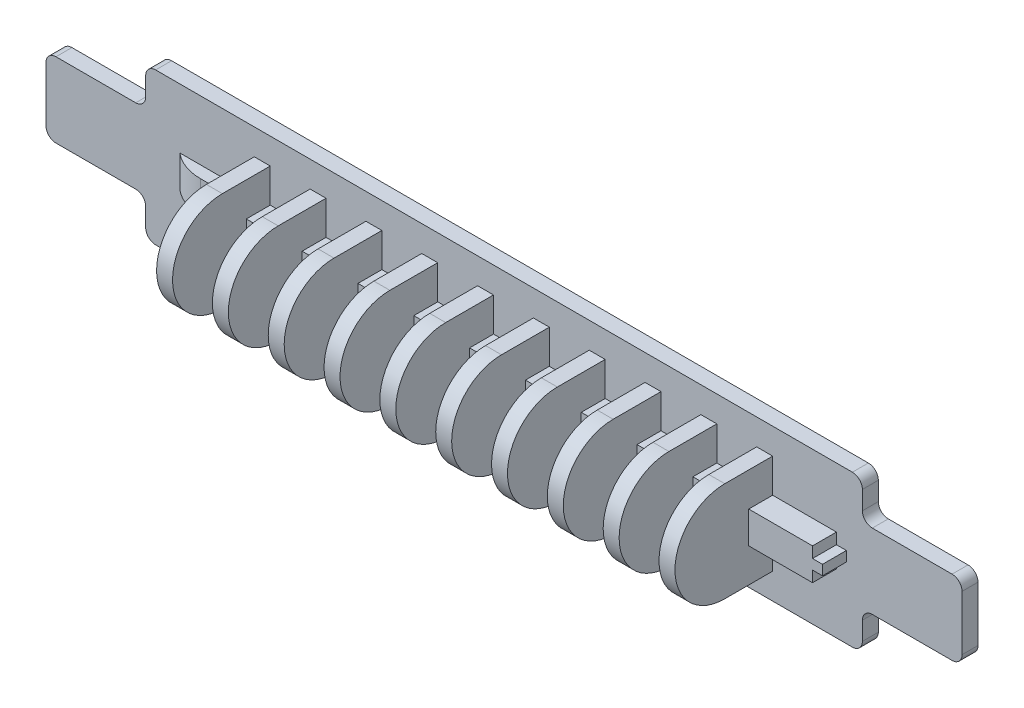
SolidWorks part; units mm, degrees
ref_plane "前视基准面" through (0, 0, 0) normal (0, 0, 1) x (1, 0, 0)
ref_plane "上视基准面" through (0, 0, 0) normal (0, 1, 0) x (1, 0, 0)
ref_plane "右视基准面" through (0, 0, 0) normal (1, 0, 0) x (0, 0, -1)
sketch "草图1" plane through (0, 0, 0) normal (0, 0, 1) x (1, 0, 0)
  line L1 (-44.9335, 9.5) -> (44.9335, 9.5)
  line L2 (-44.9335, 9.5) -> (-44.9335, -9.5)
  line L3 (-44.9335, -9.5) -> (44.9335, -9.5)
  line L4 (44.9335, 9.5) -> (44.9335, -9.5)
  line L5 (-44.9335, 9.5) -> (44.9335, -9.5) construction
  line L6 (-44.9335, -9.5) -> (44.9335, 9.5) construction
  point P0 (0, 0)
  dimension "D1" = 19
  dimension "D2" = 89.8669
extrude "凸台-拉伸1" add sketch "草图1" along normal blind 2
sketch "草图2" plane through (0, 0, 2) normal (0, 0, 1) x (1, 0, 0)
  line L0 (-44.9335, 0) -> (44.9335, 0) construction
  line L1 (-44.9335, 9.5) -> (-44.9335, -9.5) construction
  line L2 (44.9335, -9.5) -> (44.9335, 9.5) construction
  line L4 (31.6835, 6.25) -> (33.6835, 6.25)
  line L5 (31.6835, 6.25) -> (31.6835, -6.25)
  line L6 (31.6835, -6.25) -> (33.6835, -6.25)
  line L7 (33.6835, 6.25) -> (33.6835, -6.25)
  line L8 (31.6835, 6.25) -> (33.6835, -6.25) construction
  line L9 (31.6835, -6.25) -> (33.6835, 6.25) construction
  line L53 (24.6835, 6.25) -> (24.6835, -6.25)
  line L54 (24.6835, 6.25) -> (26.6835, 6.25)
  line L55 (26.6835, 6.25) -> (26.6835, -6.25)
  line L56 (24.6835, -6.25) -> (26.6835, -6.25)
  line L57 (17.6835, 6.25) -> (17.6835, -6.25)
  line L58 (17.6835, 6.25) -> (19.6835, 6.25)
  line L59 (19.6835, 6.25) -> (19.6835, -6.25)
  line L60 (17.6835, -6.25) -> (19.6835, -6.25)
  line L61 (10.6835, 6.25) -> (10.6835, -6.25)
  line L62 (10.6835, 6.25) -> (12.6835, 6.25)
  line L63 (12.6835, 6.25) -> (12.6835, -6.25)
  line L64 (10.6835, -6.25) -> (12.6835, -6.25)
  line L65 (3.6835, 6.25) -> (3.6835, -6.25)
  line L66 (3.6835, 6.25) -> (5.6835, 6.25)
  line L67 (5.6835, 6.25) -> (5.6835, -6.25)
  line L68 (3.6835, -6.25) -> (5.6835, -6.25)
  line L69 (-3.3165, 6.25) -> (-3.3165, -6.25)
  line L70 (-3.3165, 6.25) -> (-1.3165, 6.25)
  line L71 (-1.3165, 6.25) -> (-1.3165, -6.25)
  line L72 (-3.3165, -6.25) -> (-1.3165, -6.25)
  line L73 (-10.3165, 6.25) -> (-10.3165, -6.25)
  line L74 (-10.3165, 6.25) -> (-8.3165, 6.25)
  line L75 (-8.3165, 6.25) -> (-8.3165, -6.25)
  line L76 (-10.3165, -6.25) -> (-8.3165, -6.25)
  line L77 (-17.3165, 6.25) -> (-17.3165, -6.25)
  line L78 (-17.3165, 6.25) -> (-15.3165, 6.25)
  line L79 (-15.3165, 6.25) -> (-15.3165, -6.25)
  line L80 (-17.3165, -6.25) -> (-15.3165, -6.25)
  line L81 (-24.3165, 6.25) -> (-24.3165, -6.25)
  line L82 (-24.3165, 6.25) -> (-22.3165, 6.25)
  line L83 (-22.3165, 6.25) -> (-22.3165, -6.25)
  line L84 (-24.3165, -6.25) -> (-22.3165, -6.25)
  line L85 (-31.3165, 6.25) -> (-31.3165, -6.25)
  line L86 (-31.3165, 6.25) -> (-29.3165, 6.25)
  line L87 (-29.3165, 6.25) -> (-29.3165, -6.25)
  line L88 (-31.3165, -6.25) -> (-29.3165, -6.25)
  point P6 (32.6835, 0)
  dimension "D1" = 12.25
  dimension "D3" = 12.5
  dimension "D4" = 2
  dimension "D2" = 10
extrude "凸台-拉伸2" add sketch "草图2" along normal blind 6
sketch "草图3" plane through (0, 0, 2) normal (0, 0, 1) x (1, 0, 0)
  line L0 (-44.9335, 0) -> (44.9335, 0) construction
  line L1 (-44.9335, 9.5) -> (-44.9335, -9.5) construction
  line L2 (44.9335, -9.5) -> (44.9335, 9.5) construction
  line L6 (-29.3165, -2) -> (42.9335, -2)
  line L7 (42.9335, 2) -> (42.9335, -2)
  line L8 (-36.3165, 2) -> (42.9335, 2)
  line L9 (-29.3165, -2) -> (-36.3165, -2)
  line L12 (-36.3165, -2) -> (-36.3165, 2)
  dimension "D1" = 2
extrude "凸台-拉伸3" add sketch "草图3" along normal blind 3
sketch "草图4" plane through (0, 0, 8) normal (0, 0, 1) x (1, 0, 0)
  line L0 (-31.3165, 0) -> (33.6835, 0) construction
  line L101 (-31.3165, 6.25) -> (-31.3165, -6.25) construction
  line L102 (33.6835, -6.25) -> (33.6835, 6.25) construction
  line L103 (26.6835, 0) -> (26.6835, -6.25)
  line L104 (33.6835, 0) -> (31.6835, 0)
  line L105 (33.6835, 0) -> (33.6835, -6.25)
  line L106 (33.6835, -6.25) -> (31.6835, -6.25)
  line L107 (31.6835, 0) -> (31.6835, -6.25)
  line L108 (26.6835, 0) -> (24.6835, 0)
  line L109 (24.6835, 0) -> (24.6835, -6.25)
  line L110 (26.6835, -6.25) -> (24.6835, -6.25)
  line L111 (19.6835, 0) -> (19.6835, -6.25)
  line L112 (19.6835, 0) -> (17.6835, 0)
  line L113 (17.6835, 0) -> (17.6835, -6.25)
  line L114 (19.6835, -6.25) -> (17.6835, -6.25)
  line L115 (12.6835, 0) -> (12.6835, -6.25)
  line L116 (12.6835, 0) -> (10.6835, 0)
  line L117 (10.6835, 0) -> (10.6835, -6.25)
  line L118 (12.6835, -6.25) -> (10.6835, -6.25)
  line L119 (5.6835, 0) -> (5.6835, -6.25)
  line L120 (5.6835, 0) -> (3.6835, 0)
  line L121 (3.6835, 0) -> (3.6835, -6.25)
  line L122 (5.6835, -6.25) -> (3.6835, -6.25)
  line L123 (-1.3165, 0) -> (-1.3165, -6.25)
  line L124 (-1.3165, 0) -> (-3.3165, 0)
  line L125 (-3.3165, 0) -> (-3.3165, -6.25)
  line L126 (-1.3165, -6.25) -> (-3.3165, -6.25)
  line L127 (-8.3165, 0) -> (-8.3165, -6.25)
  line L128 (-8.3165, 0) -> (-10.3165, 0)
  line L129 (-10.3165, 0) -> (-10.3165, -6.25)
  line L130 (-8.3165, -6.25) -> (-10.3165, -6.25)
  line L131 (-15.3165, 0) -> (-15.3165, -6.25)
  line L132 (-15.3165, 0) -> (-17.3165, 0)
  line L133 (-17.3165, 0) -> (-17.3165, -6.25)
  line L134 (-15.3165, -6.25) -> (-17.3165, -6.25)
  line L135 (-22.3165, 0) -> (-22.3165, -6.25)
  line L136 (-22.3165, 0) -> (-24.3165, 0)
  line L137 (-24.3165, 0) -> (-24.3165, -6.25)
  line L138 (-22.3165, -6.25) -> (-24.3165, -6.25)
  line L139 (-29.3165, 0) -> (-29.3165, -6.25)
  line L140 (-29.3165, 0) -> (-31.3165, 0)
  line L141 (-31.3165, 0) -> (-31.3165, -6.25)
  line L142 (-29.3165, -6.25) -> (-31.3165, -6.25)
  dimension "D1" = 10
revolve "旋转1" add sketch "草图4" angle 180 about L0
sketch "草图11" plane through (0, -2, 0) normal (0, -1, 0) x (1, 0, 0)
  line L4 (42.9335, 5) -> (33.6835, 5)
  line L16 (42.9335, 5) -> (33.6835, 5)
  line L20 (33.6835, 5) -> (33.6835, 2)
  line L22 (33.6835, 5) -> (33.6835, 2)
  line L24 (33.6835, 2) -> (42.9335, 2)
  line L25 (33.6835, 2) -> (42.9335, 2)
  line L26 (42.9335, 2) -> (42.9335, 5)
  line L27 (42.9335, 2) -> (42.9335, 5)
  dimension "D1" = 0
extrude "凸台-拉伸8" add sketch "草图11" along normal blind 1.5 and the other way blind 3.5
scale "缩放比例1" scale about centroid uniform scaling yes scale factor 1.6
sketch "草图13" plane through (0, -5.59, 0) normal (0, -1, 0) x (1, 0, 0)
  line L3 (53.2248, 0.8833) -> (68.0248, 0.8833)
  line L4 (53.2248, 5.6833) -> (53.2248, 0.8833)
  line L6 (53.2248, 0.8833) -> (68.0248, 0.8833)
  line L16 (53.2248, 5.6833) -> (53.2248, 0.8833)
  line L19 (68.0248, 0.8833) -> (68.0248, 5.6833)
  line L21 (68.0248, 0.8833) -> (68.0248, 5.6833)
  line L22 (68.0248, 5.6833) -> (53.2248, 5.6833)
  line L23 (68.0248, 5.6833) -> (53.2248, 5.6833)
  dimension "D1" = 0
extrude "切除-拉伸3" cut sketch "草图13" against normal up to surface (2.4 mm away)
sketch "草图16" plane through (0, 0, 5.6833) normal (0, 0, 1) x (1, 0, 0)
  line L0 (68.0248, 0.01) -> (53.2248, 0.01) construction
  line L1 (68.0248, -3.19) -> (68.0248, 3.21) construction
  line L2 (53.2248, -9.99) -> (53.2248, 10.01) construction
  line L8 (68.0248, -0.99) -> (66.0248, -0.99)
  line L9 (68.0248, 3.21) -> (66.0248, 3.21)
  line L10 (68.0248, 3.21) -> (68.0248, 1.01)
  line L11 (68.0248, 1.01) -> (66.0248, 1.01)
  line L12 (66.0248, 3.21) -> (66.0248, 1.01)
  line L13 (66.0248, -3.19) -> (66.0248, -0.99)
  line L14 (68.0248, -3.19) -> (66.0248, -3.19)
  line L15 (68.0248, -3.19) -> (68.0248, -0.99)
  dimension "D1" = 1
  dimension "D2" = 2
extrude "切除-拉伸5" cut sketch "草图16" against normal up to surface (4.8 mm away) up to face at (1.3867, 0.01, 0.8833)
sketch "草图17" plane through (0, 0, 0) normal (0, 1, 0) x (1, 0, 0)
  line L4 (-58.7752, -5.6833) -> (-58.7752, -0.8833)
  line L5 (-67.4451, -0.8833) -> (-58.7752, -0.8833)
  arc A1 (-58.7752, -5.6833) -> (-67.4451, -0.8833) centre (-58.7752, 4.5467) cw
extrude "凸台-拉伸10" add sketch "草图17" along normal up to surface and the other way up to surface
sketch "草图18" plane through (0, 3.21, 0) normal (0, 1, 0) x (1, 0, 0)
  line L1 (-50.7752, -5.6833) -> (-50.7752, -0.8833) construction
  line L2 (-50.7752, -3.2833) -> (-59.1535, -3.2833)
  line L3 (-50.7752, -0.8833) -> (-67.4451, -0.8833) construction
  line L4 (-50.7752, -5.6833) -> (-58.7752, -5.6833) construction
  line L5 (-65.7144, -0.8833) -> (-67.4451, -0.8833)
  line L6 (-50.7752, -5.6833) -> (-58.7752, -5.6833)
  line L7 (-50.7752, -3.2833) -> (-50.7752, -5.6833)
  arc A0 (-59.1535, -3.2833) -> (-65.7144, -0.8833) centre (-59.1535, 6.8847) cw
  arc A1 (-67.4451, -0.8833) -> (-58.7752, -5.6833) centre (-58.7752, 4.5467) ccw construction
  arc A2 (-67.4451, -0.8833) -> (-58.7752, -5.6833) centre (-58.7752, 4.5467) ccw
extrude "切除-拉伸6" cut sketch "草图18" against normal up to surface (6.4 mm away)
fillet "圆角1" radius 2 4 edges at (71.2248, -15.19, -0.7167) (71.2248, 15.21, -0.7167) (-72.5622, 15.21, -0.7167) (-72.5622, -15.19, -0.7167)
sketch "草图19" plane through (0, 0, -2.3167) normal (0, 0, -1) x (-1, 0, 0)
  line L0 (0, 40.8917) -> (0, -48.5133) construction
  line L1 (-111.5136, 0) -> (108.2026, 0) construction
  line L2 (-71.2248, -13.19) -> (-71.2248, 13.21) construction
  line L3 (-71.2248, 7.5) -> (-91.2248, 7.5)
  line L4 (-71.2248, 7.5) -> (-71.2248, -7.5)
  line L5 (-71.2248, -7.5) -> (-91.2248, -7.5)
  line L6 (-91.2248, 7.5) -> (-91.2248, -7.5)
  line L7 (72.5622, 13.21) -> (72.5622, -13.19) construction
  line L8 (72.5622, 7.5) -> (92.5622, 7.5)
  line L9 (72.5622, 7.5) -> (72.5622, -7.5)
  line L10 (72.5622, -7.5) -> (92.5622, -7.5)
  line L11 (92.5622, 7.5) -> (92.5622, -7.5)
  dimension "D1" = 20
  dimension "D2" = 15
  dimension "D3" = 15
  dimension "D4" = 20
extrude "凸台-拉伸11" add sketch "草图19" against normal up to surface (3.2 mm away) up to face at (4.1671, 0.01, 0.8833)
fillet "圆角2" radius 2 8 edges at (-72.5622, 7.5, -0.7167) (-92.5622, 7.5, -0.7167) (-92.5622, -7.5, -0.7167) (-72.5622, -7.5, -0.7167) (71.2248, -7.5, -0.7167) (91.2248, -7.5, -0.7167) (91.2248, 7.5, -0.7167) (71.2248, 7.5, -0.7167)
